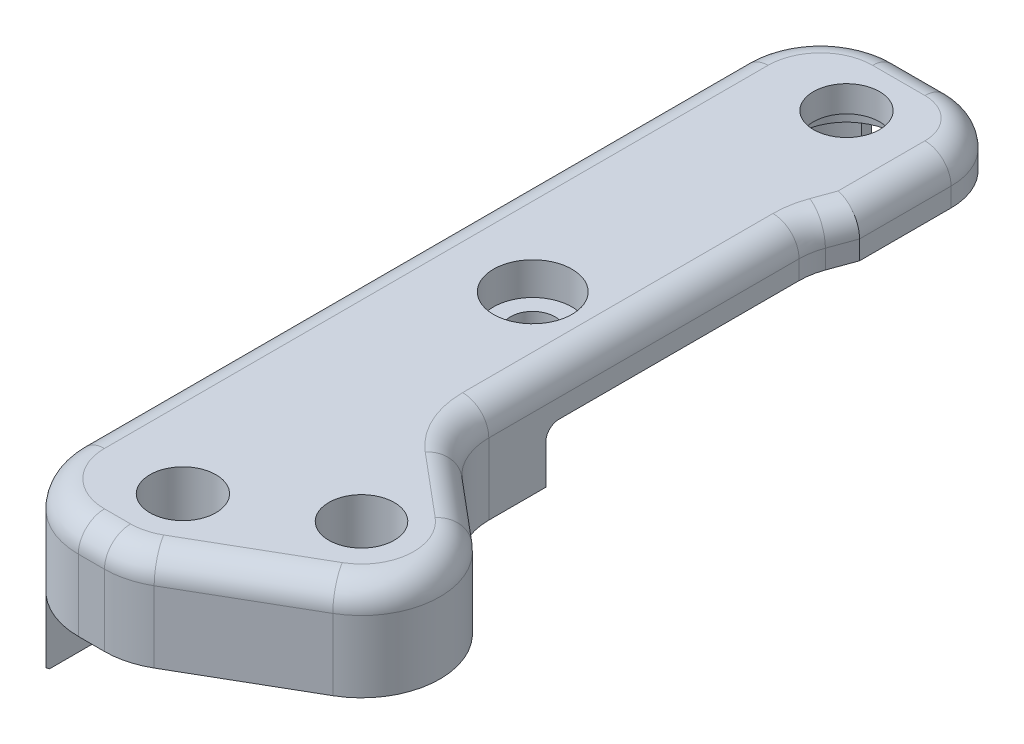
SolidWorks part; units mm, degrees
ref_plane "前视基准面" through (0, 0, 0) normal (0, 0, 1) x (1, 0, 0)
ref_plane "上视基准面" through (0, 0, 0) normal (0, 1, 0) x (1, 0, 0)
ref_plane "右视基准面" through (0, 0, 0) normal (1, 0, 0) x (0, 0, -1)
other "Configuration Table"
ref_plane "基准面1" through (0, 17.55, 0) normal (0, -1, 0) x (1, 0, 0)
sketch "草图1" plane through (0, 17.55, 0) normal (0, -1, 0) x (1, 0, 0)
  line L0 (-8, -56.7543) -> (6, -56.7543)
  line L1 (6, -56.7543) -> (6, -15.0647)
  line L2 (6, -15.0647) -> (12.517, -9.5963)
  line L3 (11.6603, 0.1962) -> (1.6077, 6)
  line L4 (1.6077, 6) -> (-8, 6)
  line L5 (-8, 6) -> (-8, -56.7543)
  arc A0 (12.517, -9.5963) -> (11.6603, 0.1962) centre (8.6603, -5) ccw
  dimension "D1" = 6
  dimension "D2" = 9.6077
  dimension "D3" = 14
  dimension "D4" = 16.6603
  dimension "D5" = 19.6603
  dimension "D6" = 20.517
  dimension "D7" = 41.6896
extrude "凸台-拉伸1" add sketch "草图1" against normal blind 7.45
ref_plane "基准面2" through (0, 25, 0) normal (0, 1, 0) x (1, 0, 0)
sketch "草图2" plane through (0, 25, 0) normal (0, 1, 0) x (1, 0, 0)
  line L0 (6, 56.7543) -> (6, 42.0068)
  line L1 (6, 42.0068) -> (7, 44.7543)
  line L2 (7, 44.7543) -> (7, 56.7543)
  line L3 (7, 56.7543) -> (6, 56.7543)
  dimension "D1" = 1
  dimension "D2" = 12
  dimension "D3" = 14.7475
extrude "凸台-拉伸2" add sketch "草图2" against normal blind 3.45
sketch "草图3" plane through (6, 0, 0) normal (1, 0, 0) x (0, 0, -1)
  line L0 (21.7543, 21.55) -> (21.7543, 17.55)
  line L1 (21.7543, 17.55) -> (56.7543, 17.55)
  line L2 (56.7543, 17.55) -> (56.7543, 21.55)
  line L3 (56.7543, 21.55) -> (21.7543, 21.55)
  line L4 (15.0647, 25) -> (15.0647, 17.55) construction
  line L5 (42.0068, 25) -> (15.0647, 25) construction
  dimension "D1" = 6.6896
  dimension "D2" = 41.6896
  dimension "D3" = 3.45
  dimension "D4" = 7.45
extrude "切除-拉伸1" cut sketch "草图3" against normal blind 9.8
sketch "草图4" plane through (0, 17.55, 0) normal (0, -1, 0) x (1, 0, 0)
  line L0 (-3.8, 6) -> (-3.8, -56.7543)
  line L1 (-3.8, -56.7543) -> (-8, -56.7543)
  line L2 (-8, -56.7543) -> (-8, 6)
  line L3 (-8, 6) -> (-3.8, 6)
  line L4 (6, -21.7543) -> (6, -15.0647) construction
  dimension "D1" = 9.8
  dimension "D2" = 14
  dimension "D3" = 62.7543
extrude "凸台-拉伸3" add sketch "草图4" along normal blind 5.05
sketch "草图5" plane through (0, 21.55, 0) normal (0, -1, 0) x (1, 0, 0)
  line L0 (-2.5, -30.7543) -> (-3.8, -30.7543)
  line L1 (-3.8, -30.7543) -> (-3.8, -50.7543)
  line L2 (-2.5, -46.9477) -> (-2.5, -30.7543)
  line L3 (7, -44.7543) -> (7, -56.7543) construction
  line L4 (7, -56.7543) -> (-3.8, -56.7543) construction
  arc A0 (-3.8, -50.7543) -> (-1.7674, -47.3904) centre (0, -50.7543) ccw
  arc A1 (-1.7674, -47.3904) -> (-2.5, -46.9477) centre (-2, -46.9477) cw
  dimension "D1" = 3.8
  dimension "D2" = 0.5
  dimension "D3" = 7
  dimension "D4" = 8.7674
  dimension "D5" = 6
  dimension "D8" = 26
extrude "切除-拉伸2" cut sketch "草图5" against normal blind 1.45
sketch "草图6" plane through (0, 17.55, 0) normal (0, -1, 0) x (1, 0, 0)
  line L0 (4, -12) -> (-3.8, -12)
  line L1 (-3.8, -12) -> (-3.8, -8)
  line L2 (-3.8, -8) -> (4, -8)
  line L3 (4, -8) -> (4, -12)
  line L4 (-3.8, -21.7543) -> (-3.8, 6) construction
  line L5 (-3.8, -21.7543) -> (6, -21.7543) construction
  dimension "D1" = 7.8
  dimension "D2" = 9.7543
  dimension "D3" = 13.7543
extrude "凸台-拉伸4" add sketch "草图6" along normal blind 5.05
ref_plane "基准面3" through (-3.8, 0, 0) normal (1, 0, 0) x (0, 0, -1)
ref_plane "基准面4" through (-6, 0, 0) normal (-1, 0, 0) x (0, -1, 0)
sketch "草图8" plane through (-6, 0, 0) normal (-1, 0, 0) x (0, -1, 0)
  line L0 (-12.5, -12) -> (-17.55, -12)
  line L1 (-17.55, -12) -> (-17.55, -24)
  line L2 (-17.55, -24) -> (-12.5, -24)
  line L3 (-12.5, -24) -> (-12.5, -12)
  dimension "D1" = 5.05
  dimension "D2" = 12
extrude "切除-拉伸3" cut sketch "草图8" against normal up to surface up to plane "基准面3"
sketch "草图9" plane through (-3.8, 0, 0) normal (1, 0, 0) x (0, 0, -1)
  line L0 (8, 17.55) -> (-6, 17.55)
  line L1 (-6, 17.55) -> (-6, 12.5)
  line L2 (-6, 12.5) -> (8, 12.5)
  line L3 (8, 12.5) -> (8, 17.55)
  line L4 (8, 12.5) -> (8, 17.55) construction
  line L5 (8, 12.5) -> (-6, 12.5) construction
  dimension "D1" = 14
  dimension "D2" = 5.05
extrude "切除-拉伸4" cut sketch "草图9" against normal blind 2.2
sketch "草图10" plane through (0, 12.5, 0) normal (0, -1, 0) x (1, 0, 0)
  line L0 (-3.8, -55.7164) -> (-3.8, -45.7922)
  line L1 (-8, 6) -> (-8, -56.7543) construction
  arc A0 (-3.8, -45.7922) -> (-3.8, -55.7164) centre (0, -50.7543) ccw
  dimension "D1" = 6.25
  dimension "D2" = 4.2
  dimension "D3" = 8
  dimension "D4" = 51.7922
extrude "切除-拉伸5" cut sketch "草图10" against normal blind 9.05
hole_wizard "孔1" positions "草图12" profile "草图11" legacy
sketch "草图12" plane through (0, 17.55, 0) normal (0, -1, 0) x (-1, 0, 0)
  point P0 (-8.6603, 5)
sketch "草图11" plane through (8.6603, 17.55, -5) normal (1, 0, 0) x (0, 0, -1)
  line L0 (0, 0) -> (0, 7.45)
  line L1 (0, 7.45) -> (2.505, 7.45)
  line L2 (2.505, 7.45) -> (2.505, 0)
  line L3 (2.505, 0) -> (0, 0)
  line L4 (0, 110) -> (0, -10) construction
  dimension "直径" = 5.01
  dimension "深度" = 7.45
hole_wizard "孔2" positions "草图14" profile "草图13" legacy
sketch "草图14" plane through (0, 17.55, 0) normal (0, -1, 0) x (-1, 0, 0)
  point P0 (0, 0)
sketch "草图13" plane through (0, 17.55, 0) normal (1, 0, 0) x (0, 0, -1)
  line L0 (0, 0) -> (0, 7.45)
  line L1 (0, 7.45) -> (2.525, 7.45)
  line L2 (2.525, 7.45) -> (2.525, 0)
  line L3 (2.525, 0) -> (0, 0)
  line L4 (0, 110) -> (0, -10) construction
  dimension "直径" = 5.05
  dimension "深度" = 7.45
hole_wizard "孔3" positions "草图16" profile "草图15" legacy
sketch "草图16" plane through (0, 23, 0) normal (0, -1, 0) x (-1, 0, 0)
  point P0 (0, 50.7543)
sketch "草图15" plane through (0, 23, -50.7543) normal (1, 0, 0) x (0, 0, -1)
  line L0 (0, 0) -> (0, 2)
  line L1 (0, 2) -> (2.525, 2)
  line L2 (2.525, 2) -> (2.525, 0)
  line L3 (2.525, 0) -> (0, 0)
  line L4 (0, 110) -> (0, -10) construction
  dimension "直径" = 5.05
  dimension "深度" = 2
hole_wizard "孔4" positions "草图18" profile "草图17" legacy
sketch "草图18" plane through (0, 25, 0) normal (0, 1, 0) x (1, 0, 0)
  point P0 (0, 26.7543)
sketch "草图17" plane through (0, 25, -26.7543) normal (1, 0, 0) x (0, 0, 1)
  line L0 (0, 0) -> (0, 12.5)
  line L1 (0, 12.5) -> (1.7, 12.5)
  line L2 (1.7, 12.5) -> (1.7, 2.5)
  line L3 (1.7, 2.5) -> (3, 2.5)
  line L4 (3, 2.5) -> (3, 0)
  line L5 (3, 0) -> (0, 0)
  line L6 (0, 110) -> (0, -10) construction
  dimension "直径" = 3.4
  dimension "深度" = 12.5
  dimension "柱坑直径" = 6
  dimension "柱坑深度" = 2.5
fillet "圆角1" radius 5 3 edges at (6, 23.275, -42.0068) (7, 23.275, -56.7543) (6, 21.275, -15.0647)
fillet "圆角2" radius 6 3 edges at (-8, 18.75, -56.7543) (-8, 18.75, 6) (1.6077, 21.275, 6)
chamfer "倒角1" distance 0.2 angle 45 3 edges at (-7.4772, 12.5, 2.4495) (-8, 12.5, -25.3772) (-6.8374, 12.5, -54.304)
fillet "圆角3" radius 0.5 2 edges at (-2.5, 22.275, -30.7543) (-3.8, 22.275, -30.7543)
fillet "圆角4" radius 1 4 edges at (-1, 17.55, -8) (-4.9, 17.55, -24) (1.1, 21.55, -21.7543) (-1, 17.55, -12)
fillet "圆角5" radius 2 15 edges at (7, 25, -48.2543) (6.6508, 25, -43.7948) (5.5355, 25, -55.2898) (6.076, 25, -41.9934) (0, 25, -56.7543) (6, 25, -29.2607) (-6.2426, 25, -54.997) (6.4685, 25, -15.2831) (-8, 25, -25.3772) (10.1515, 25, -11.5811) (-6.2426, 25, 4.2426) (14.6374, 25, -4.4771) (-1, 25, 6) (7.3301, 25, 2.6962) (1.5529, 25, 5.7956)
